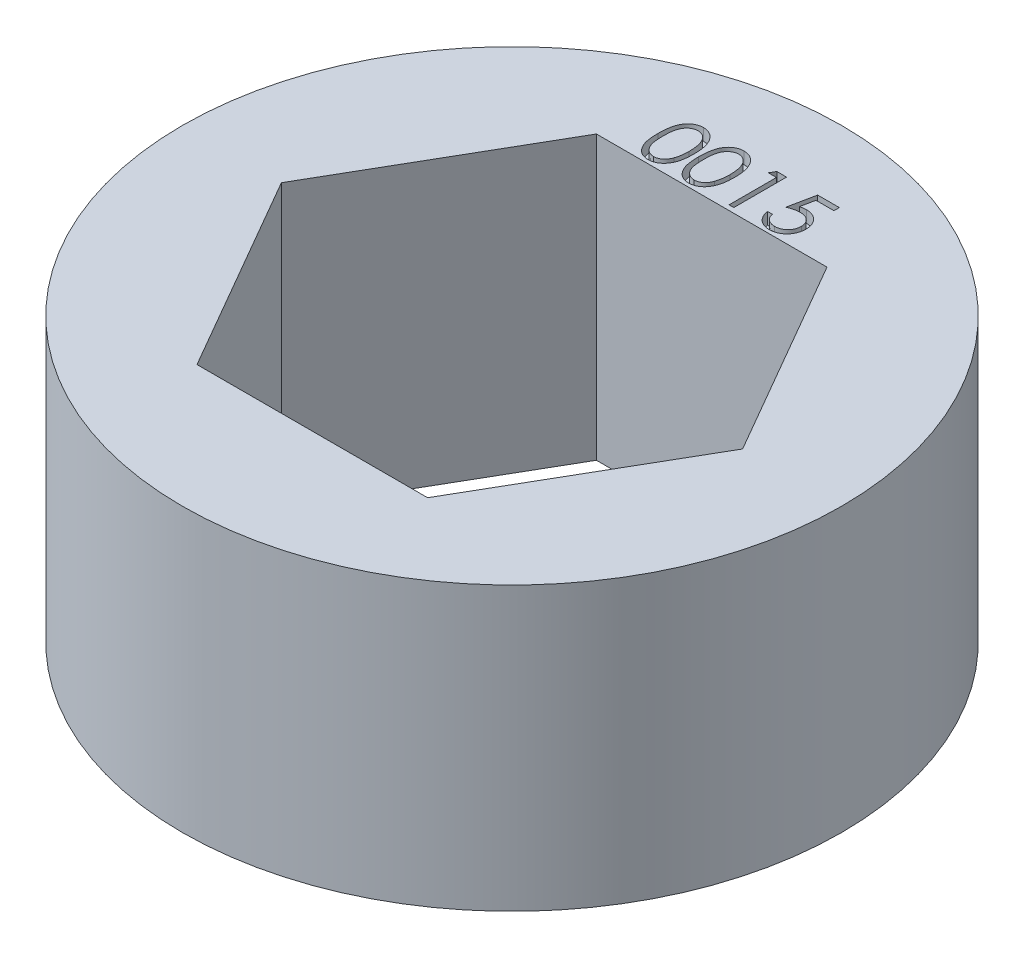
SolidWorks part; units mm, degrees
material "Nylon 101"
ref_plane "Front Plane" through (0, 0, 0) normal (0, 0, 1) x (1, 0, 0)
ref_plane "Top Plane" through (0, 0, 0) normal (0, 1, 0) x (1, 0, 0)
ref_plane "Right Plane" through (0, 0, 0) normal (1, 0, 0) x (0, 0, -1)
sketch "Sketch1" plane through (0, 0, 0) normal (0, 1, 0) x (1, 0, 0)
  line L1 (7.7723, 0) -> (3.8861, 6.731)
  line L2 (3.8861, 6.731) -> (-3.8861, 6.731)
  line L3 (-3.8861, 6.731) -> (-7.7723, 0)
  line L4 (-7.7723, 0) -> (-3.8861, -6.731)
  line L5 (-3.8861, -6.731) -> (3.8861, -6.731)
  line L6 (3.8861, -6.731) -> (7.7723, 0)
  circle A0 centre (0, 0) radius 11.1125
  circle A1 centre (0, 0) radius 6.731 construction
  dimension "D1" = 22.225
  dimension "D2" = 13.462
extrude "Boss-Extrude1" add sketch "Sketch1" along normal blind 9.525
sketch "Sketch2" plane through (0, 9.525, 0) normal (0, 1, 0) x (1, 0, 0)
  line L0 (-2.9329, 6.8988) -> (2.8897, 6.8988) construction
  line L1 (3.8861, 6.731) -> (-3.8861, 6.731) construction
  text T0 "0015" font "Century Gothic" height 1.778
  dimension "D1" = 0.1678
extrude "Cut-Extrude1" cut sketch "Sketch2" against normal blind 0.4
